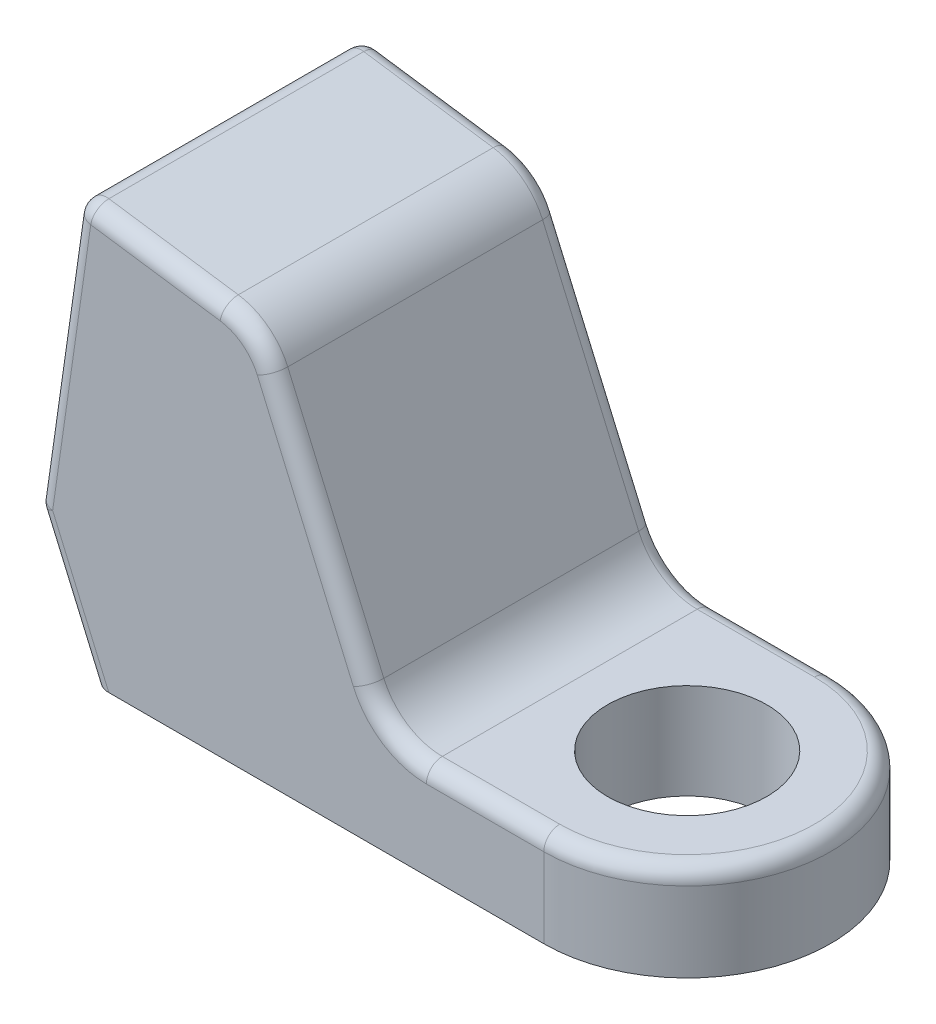
SolidWorks part; units mm, degrees
ref_plane "Front Plane" through (0, 0, 0) normal (0, 0, 1) x (1, 0, 0)
ref_plane "Top Plane" through (0, 0, 0) normal (0, 1, 0) x (1, 0, 0)
ref_plane "Right Plane" through (0, 0, 0) normal (1, 0, 0) x (0, 0, -1)
sketch "Sketch1" plane through (0, 0, 0) normal (0, 1, 0) x (1, 0, 0)
  line L1 (-7.5, -4.5) -> (8, -4.5)
  line L2 (-7.5, -4.5) -> (-7.5, 4.5)
  line L3 (-7.5, 4.5) -> (8, 4.5)
  arc A0 (8, 4.5) -> (8, -4.5) centre (8, 0) cw
  circle A1 centre (8, 0) radius 2.5
  point P0 (0, 0)
  point P4 (12.5, 0)
  dimension "D3" = 4.5
  dimension "D2" = 5
  dimension "D1" = 20
extrude "Boss-Extrude1" add sketch "Sketch1" along normal blind 3
sketch "Sketch2" plane through (0, 3, 0) normal (0, 1, 0) x (1, 0, 0)
  line L6 (3, 4.5) -> (3, -4.5)
  line L7 (3, 4.5) -> (-9.5, 4.5)
  line L8 (3, -4.5) -> (-9.5, -4.5)
  line L9 (-9.5, 4.5) -> (-9.5, -4.5)
  line L10 (8, 4.5) -> (-7.5, 4.5) construction
  line L11 (-7.5, -4.5) -> (8, -4.5) construction
  line L12 (-7.5, 4.5) -> (-7.5, -4.5) construction
  circle A1 centre (8, 0) radius 2.5 construction
  dimension "D2" = 2
  dimension "D1" = 5
extrude "Boss-Extrude2" add sketch "Sketch2" along normal blind 10
sketch "Sketch3" plane through (0, 0, 4.5) normal (0, 0, 1) x (1, 0, 0)
  line L0 (-6.2, 0) -> (-7.5, 3)
  line L1 (-7.5, 0) -> (8, 0) construction
  line L2 (-7.5, 3) -> (-7.9333, 4)
  line L3 (-6.2, 0) -> (-9.5, 0)
  line L4 (3, 3) -> (-0.9826, 12.1907)
  line L5 (3, 13) -> (3, 3) construction
  line L6 (-9.5, 13) -> (3, 13) construction
  line L7 (-7.9333, 4) -> (-7.9333, 13) construction
  line L8 (-9.5, 0) -> (-9.5, 13)
  line L11 (3, 13) -> (3, 3)
  line L12 (-7.9333, 4) -> (-6.6476, 13)
  line L13 (-7.5, 3) -> (-7.5, 0) construction
  line L14 (-6.6476, 13) -> (-0.9826, 12.1907)
  line L15 (3, 13) -> (-9.5, 13)
  line M1 (-7.5, 0) -> (8, 0)
  line M4 (3, 3) -> (3, 13)
  line M5 (3, 13) -> (-9.5, 13)
  line M6 (-9.5, 13) -> (-9.5, 3)
  line M7 (-9.5, 3) -> (-7.5, 3)
  line M8 (-7.5, 3) -> (-7.5, 0)
  dimension "D1" = 4
  dimension "D2" = 8.13
  dimension "D3" = 1.3
extrude "Cut-Extrude1" cut sketch "Sketch3" against normal blind 9 contours L2 L7 L15 M6 M7 | L7 L12 M5 | L0 M1 M8 | L8 L3 M8 M7 | L14 L4 M5 M4
sketch "Sketch5" plane through (-8.3347, 1.1907, 0) normal (-0.9899, 0.1414, 0) x (0, 0, 1)
  line L0 (0, 11.9292) -> (0, 2.8379) construction
  line L1 (-4.5, 11.9292) -> (4.5, 11.9292) construction
  line L2 (-4.5, 2.8379) -> (4.5, 2.8379) construction
  line L4 (0, 10.9335) -> (-2.7755, 9.5969)
  line L5 (-2.7755, 9.5969) -> (-3.461, 6.5936)
  line L6 (-3.461, 6.5936) -> (-1.5403, 4.1851)
  line L7 (-1.5403, 4.1851) -> (1.5403, 4.1851)
  line L8 (1.5403, 4.1851) -> (3.461, 6.5936)
  line L9 (3.461, 6.5936) -> (2.7755, 9.5969)
  line L10 (2.7755, 9.5969) -> (0, 10.9335)
  circle A0 centre (0, 7.3835) radius 3.55 construction
  dimension "D1" = 7.1
extrude "Cut-Extrude2" cut sketch "Sketch5" against normal blind 5
fillet "Fillet1" radius 2 2 edges at (3, 3, 0) (-0.9826, 12.1907, 0)
fillet "Fillet2" radius 0.5 17 edges at (-4.3689, 12.6745, -4.5) (-1.1596, 11.9589, -4.5) (0.97, 7.6845, -4.5) (3.2154, 3.3281, -4.5) (6.1565, 3, -4.5) (12.5, 3, 0) (6.1565, 3, 4.5) (3.2154, 3.3281, 4.5) (0.97, 7.6845, 4.5) (-1.1596, 11.9589, 4.5) (-4.3689, 12.6745, 4.5) (-6.6476, 13, 0) (-7.2905, 8.5, 4.5) (-7.2905, 8.5, -4.5) (-7.0667, 2, -4.5) (-7.0667, 2, 4.5) (-7.9333, 4, 0)
